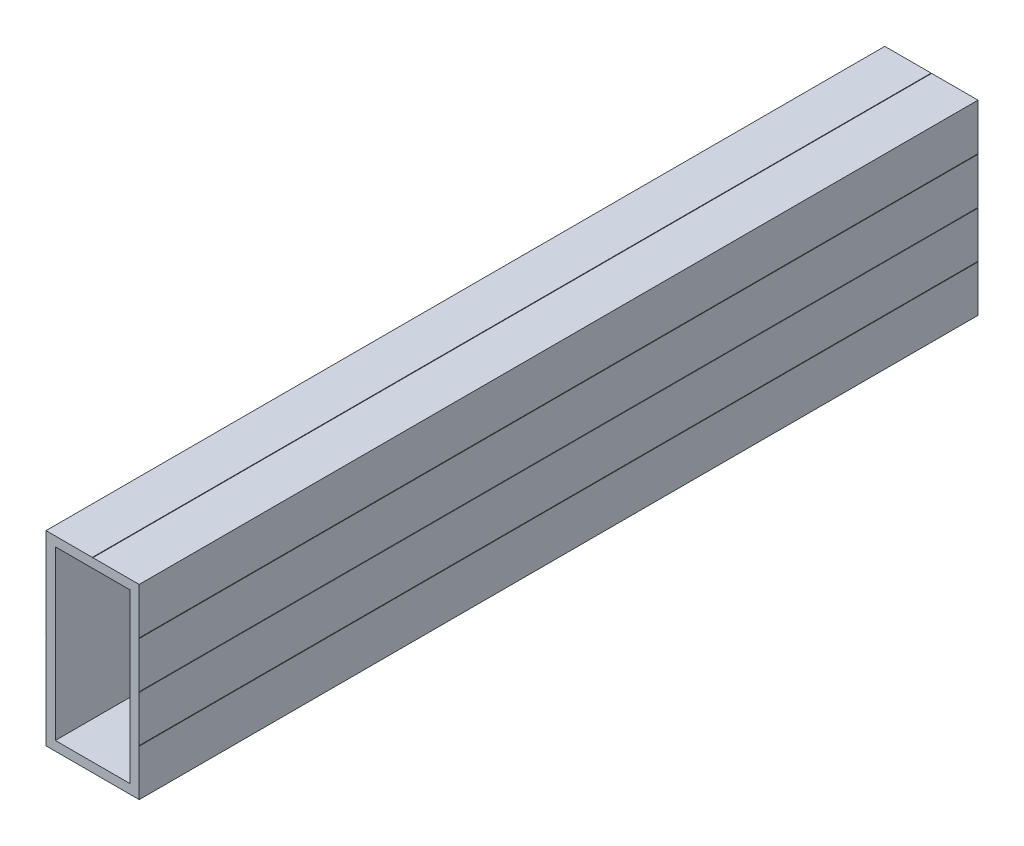
SolidWorks part; units mm, degrees
ref_plane "Front Plane" through (0, 0, 0) normal (0, 0, 1) x (1, 0, 0)
ref_plane "Top Plane" through (0, 0, 0) normal (0, 1, 0) x (1, 0, 0)
ref_plane "Right Plane" through (0, 0, 0) normal (1, 0, 0) x (0, 0, -1)
ref_plane "Plane1" through (12.7, 0, 0) normal (1, 0, 0) x (0, 0, -1)
sketch "Sketch1" plane through (12.7, 0, 0) normal (1, 0, 0) x (0, 0, -1)
  line L0 (-749.3, 25.4) -> (-749.3, -25.4)
  line L1 (-749.3, -25.4) -> (749.3, -25.4)
  line L2 (749.3, -25.4) -> (749.3, 25.4)
  line L3 (749.3, 25.4) -> (-749.3, 25.4)
extrude "Boss-Extrude1" add sketch "Sketch1" against normal blind 25.4
sketch "Sketch2" plane through (0, 0, 749.3) normal (0, 0, 1) x (1, 0, 0)
  line L0 (0.0762, 25.4) -> (-0.0762, 25.4)
  line L1 (-0.0762, 25.4) -> (0.0762, 25.2476)
  line L2 (0.0762, 25.2476) -> (0.0762, 25.4)
extrude "Cut-Extrude1" cut sketch "Sketch2" against normal blind 1498.6
sketch "Sketch3" plane through (0, 0, 749.3) normal (0, 0, 1) x (1, 0, 0)
  line L0 (12.7, 12.6238) -> (12.7, 12.7762)
  line L1 (12.7, 12.7762) -> (12.5476, 12.7762)
  line L2 (12.5476, 12.7762) -> (12.7, 12.6238)
extrude "Cut-Extrude2" cut sketch "Sketch3" against normal through all
sketch "Sketch4" plane through (0, 0, 749.3) normal (0, 0, 1) x (1, 0, 0)
  line L0 (12.7, -0.0762) -> (12.7, 0.0762)
  line L1 (12.7, 0.0762) -> (12.5476, -0.0762)
  line L2 (12.5476, -0.0762) -> (12.7, -0.0762)
extrude "Cut-Extrude3" cut sketch "Sketch4" against normal blind 1498.6
sketch "Sketch5" plane through (0, 0, 749.3) normal (0, 0, 1) x (1, 0, 0)
  line L0 (12.7, -12.7762) -> (12.7, -12.6238)
  line L1 (12.7, -12.6238) -> (12.5476, -12.6238)
  line L2 (12.5476, -12.6238) -> (12.7, -12.7762)
extrude "Cut-Extrude4" cut sketch "Sketch5" against normal blind 1498.6
sketch "Sketch6" plane through (0, 0, 749.3) normal (0, 0, 1) x (1, 0, 0)
  line L0 (0.0762, -25.4) -> (-0.0762, -25.2476)
  line L1 (-0.0762, -25.2476) -> (-0.0762, -25.4)
  line L2 (-0.0762, -25.4) -> (0.0762, -25.4)
extrude "Cut-Extrude5" cut sketch "Sketch6" against normal through all
sketch "Sketch7" plane through (0, 0, 749.3) normal (0, 0, 1) x (1, 0, 0)
  line L0 (-12.7, -12.6238) -> (-12.7, -12.7762)
  line L1 (-12.7, -12.7762) -> (-12.5476, -12.7762)
  line L2 (-12.5476, -12.7762) -> (-12.7, -12.6238)
extrude "Cut-Extrude6" cut sketch "Sketch7" against normal through all
sketch "Sketch8" plane through (0, 0, 749.3) normal (0, 0, 1) x (1, 0, 0)
  line L0 (-12.7, 0.0762) -> (-12.7, -0.0762)
  line L1 (-12.7, -0.0762) -> (-12.5476, 0.0762)
  line L2 (-12.5476, 0.0762) -> (-12.7, 0.0762)
extrude "Cut-Extrude7" cut sketch "Sketch8" against normal blind 1498.6
sketch "Sketch9" plane through (0, 0, 749.3) normal (0, 0, 1) x (1, 0, 0)
  line L0 (-12.7, 12.7762) -> (-12.7, 12.6238)
  line L1 (-12.7, 12.6238) -> (-12.5476, 12.6238)
  line L2 (-12.5476, 12.6238) -> (-12.7, 12.7762)
extrude "Cut-Extrude8" cut sketch "Sketch9" against normal blind 1498.6
sketch "Sketch10" plane through (0, 0, 749.3) normal (0, 0, 1) x (1, 0, 0)
  line L0 (10.16, -22.86) -> (10.16, 22.86)
  line L1 (10.16, 22.86) -> (-10.16, 22.86)
  line L2 (-10.16, 22.86) -> (-10.16, -22.86)
  line L3 (-10.16, -22.86) -> (10.16, -22.86)
extrude "Cut-Extrude9" cut sketch "Sketch10" against normal through all
draft "Draft1" type of draft neutral plane draft angle 45 faces to draft 1 face at (0.0762, 25.3238, 0) neutral plane through (-12.7, 25.4, -749.3) neutral plane normal (0, 1, 0) parameters "D1"=45
draft "Draft2" type of draft neutral plane draft angle 45 faces to draft 1 face at (12.6238, 12.7762, 0) neutral plane through (12.7, 0, 0) neutral plane normal (1, 0, 0) parameters "D1"=45
draft "Draft3" type of draft neutral plane draft angle 45 faces to draft 1 face at (-0.0762, -25.3238, 0) neutral plane through (-12.7, -25.4, 749.3) neutral plane normal (0, -1, 0) parameters "D1"=45
draft "Draft4" type of draft neutral plane draft angle 45 faces to draft 1 face at (-12.6238, -12.7762, 0) neutral plane through (-12.7, 0, 0) neutral plane normal (-1, 0, 0) parameters "D1"=45
draft "Draft5" type of draft neutral plane draft angle 45 faces to draft 2 face at (12.6238, -12.6238, 0) face at (12.6238, 0, 0) neutral plane through (12.7, 0, 0) neutral plane normal (1, 0, 0) parameters "D1"=45
draft "Draft6" type of draft neutral plane draft angle 45 faces to draft 2 face at (-12.6238, 0, 0) face at (-12.6238, 12.6238, 0) neutral plane through (-12.7, 0, 0) neutral plane normal (-1, 0, 0) parameters "D1"=45
sketch "Sketch11" plane through (0, 0, -749.3) normal (0, 0, -1) x (-1, 0, 0)
  line L1 (28.0564, 44.6652) -> (-33.9059, 44.6652)
  line L2 (28.0564, 44.6652) -> (28.0564, -44.0138)
  line L3 (28.0564, -44.0138) -> (-33.9059, -44.0138)
  line L4 (-33.9059, 44.6652) -> (-33.9059, -44.0138)
extrude "Cut-Extrude10" cut sketch "Sketch11" against normal blind 1270
